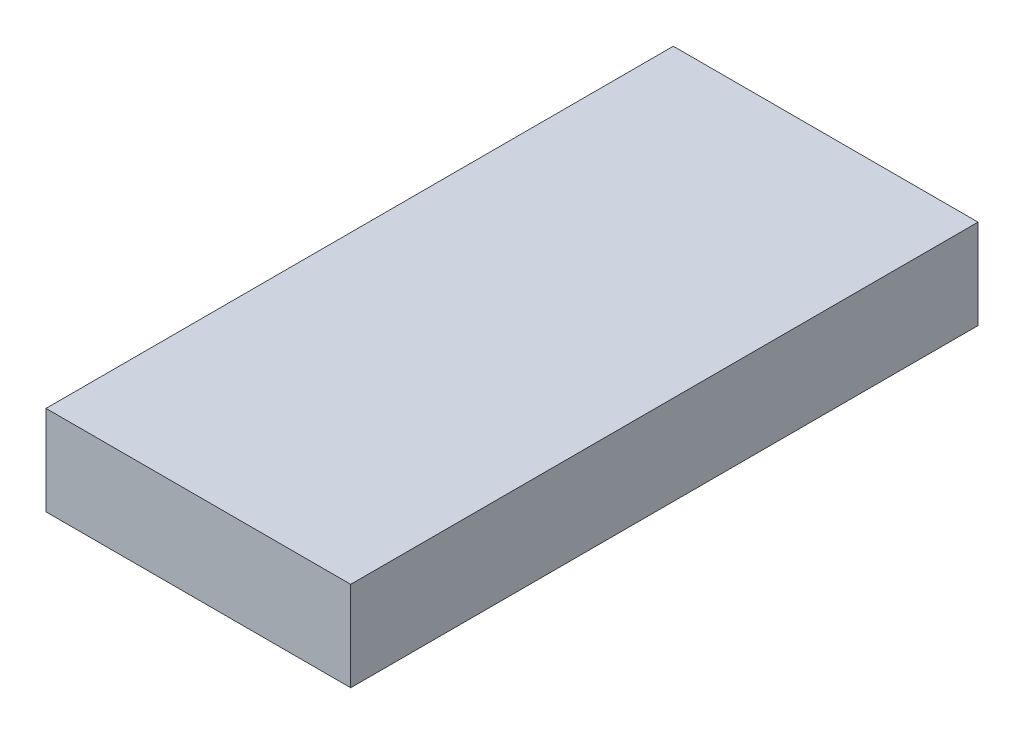
SolidWorks part; units mm, degrees
ref_plane "Front Plane" through (0, 0, 0) normal (0, 0, 1) x (1, 0, 0)
ref_plane "Top Plane" through (0, 0, 0) normal (0, 1, 0) x (1, 0, 0)
ref_plane "Right Plane" through (0, 0, 0) normal (1, 0, 0) x (0, 0, -1)
sketch "Sketch2" plane through (0, 0, 0) normal (0, 1, 0) x (1, 0, 0)
  line L0 (-279.9509, 0) -> (13717.5932, 0) construction
  line L1 (0, -279.9509) -> (0, 13717.5932) construction
  line L3 (-8.5, 17.5) -> (8.5, 17.5)
  line L4 (-8.5, 17.5) -> (-8.5, -17.5)
  line L5 (-8.5, -17.5) -> (8.5, -17.5)
  line L6 (8.5, 17.5) -> (8.5, -17.5)
  line L7 (-8.5, 17.5) -> (8.5, -17.5) construction
  line L8 (-8.5, -17.5) -> (8.5, 17.5) construction
  point P4 (0, 0)
  dimension "D1" = 17
  dimension "D2" = 35
extrude "Boss-Extrude1" add sketch "Sketch2" along normal blind 5
equation "\"Frame_Size\" = 220"
equation "\"Frame_Thickness\" = 6"
equation "\"Arm_Width\" = 30"
equation "\"Motor_Mount_Hole_Diameter\" = 8"
equation "\"Motor_Shaft_Diameter\" = 3"
equation "\"Screw_Nut_Diameter\" = 6.5"
equation "\"Screw_Diameter\" = 3"
equation "\"Screw_Shaft_Length\" = 8"
equation "\"Screw_Hole_Separation_C2C\" = 20"
equation "\"Solder_Board_Small_Screw_Hole_Separation\" = 37"
equation "\"Solder_Board_Small_Screw_Hole_Diameter\" = 3.3"
equation "\"Solder_Board_Small_Length\" = 45.72"
equation "\"Solder_Board_Small_Width\" = 33.02"
equation "\"Solder_Board_Small_Thickness\" = 1.6"
equation "\"ESC_Length\" = 35"
equation "\"ESC_Width\" = 17"
equation "\"ESC_Thickness\" = 5"
equation "\"D1@Sketch2\"=\"ESC_Width\""
equation "\"D2@Sketch2\"=\"ESC_Length\""
equation "\"D1@Boss-Extrude1\"=\"ESC_Thickness\""
